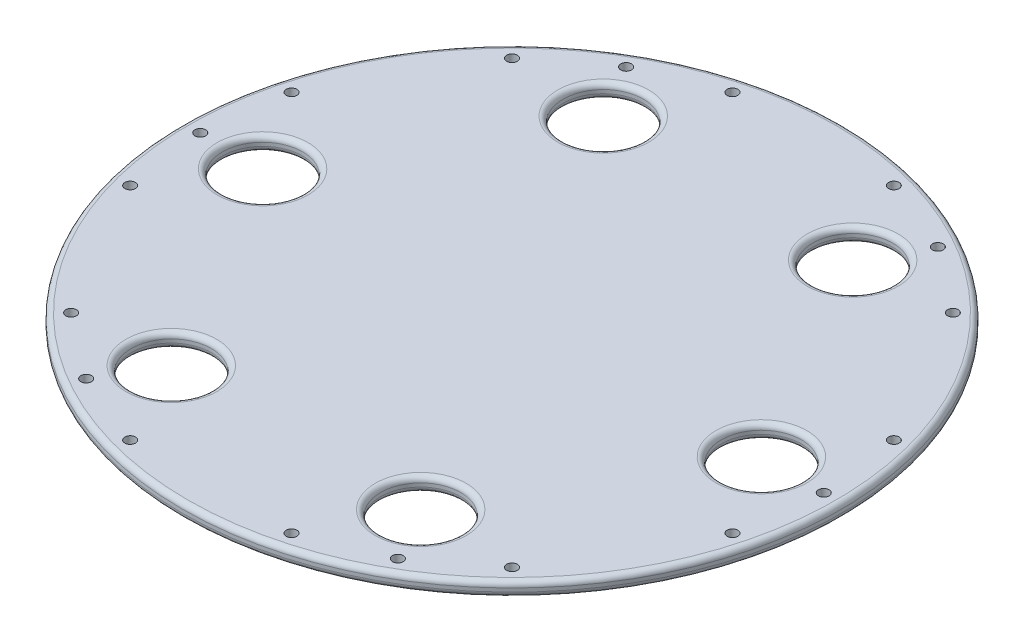
SolidWorks part; units mm, degrees
ref_plane "Front Plane" through (0, 0, 0) normal (0, 0, 1) x (1, 0, 0)
ref_plane "Top Plane" through (0, 0, 0) normal (0, 1, 0) x (1, 0, 0)
ref_plane "Right Plane" through (0, 0, 0) normal (1, 0, 0) x (0, 0, -1)
sketch "Sketch1" plane through (0, 0, 0) normal (0, 1, 0) x (1, 0, 0)
  circle A0 centre (0, 0) radius 92.5
  dimension "D1" = 185
extrude "Boss-Extrude1" add sketch "Sketch1" along normal blind 4
sketch "Sketch2" plane through (0, 4, 0) normal (0, 1, 0) x (1, 0, 0)
  line L0 (0, 0) -> (-51, 0)
  line L1 (0, 0) -> (-43.75, 75.7772)
  line L4 (0, 0) -> (-7, 0)
  line L5 (0, 0) -> (-35, 60.6218)
  circle A3 centre (-43.75, 75.7772) radius 1.5
  circle A4 centre (-22.6467, 84.5185) radius 1.5
  circle A5 centre (-61.8718, 61.8718) radius 1.5
  circle A6 centre (43.75, 75.7772) radius 1.5
  circle A7 centre (22.6467, 84.5185) radius 1.5
  circle A8 centre (61.8718, 61.8718) radius 1.5
  circle A9 centre (87.5, 0) radius 1.5
  circle A10 centre (84.5185, 22.6467) radius 1.5
  circle A11 centre (84.5185, -22.6467) radius 1.5
  circle A13 centre (-35, 60.6218) radius 11.25
  circle A23 centre (35, 60.6218) radius 11.25
  circle A24 centre (70, 0) radius 11.25
  circle A25 centre (43.75, -75.7772) radius 1.5
  circle A26 centre (61.8718, -61.8718) radius 1.5
  circle A27 centre (22.6467, -84.5185) radius 1.5
  circle A28 centre (-43.75, -75.7772) radius 1.5
  circle A29 centre (-22.6467, -84.5185) radius 1.5
  circle A30 centre (-61.8718, -61.8718) radius 1.5
  circle A31 centre (-87.5, 0) radius 1.5
  circle A32 centre (-84.5185, -22.6467) radius 1.5
  circle A33 centre (-84.5185, 22.6467) radius 1.5
  circle A34 centre (35, -60.6218) radius 11.25
  circle A35 centre (-35, -60.6218) radius 11.25
  circle A36 centre (-70, 0) radius 11.25
  point P10 (0, 0)
  point P15 (0, 0)
  point P18 (0, 0)
  point P32 (0, 0)
  point P33 (0, 0)
  point P41 (0, 0)
  point P46 (0, 0)
  point P49 (0, 0)
  point P55 (0, 0)
  dimension "D1" = 70
  dimension "D2" = 6
  dimension "D5" = 2
  dimension "D6" = 2
  dimension "D7" = 3
  dimension "D8" = 6
  dimension "D4" = 22.5
  dimension "D3" = 60
extrude "Cut-Extrude1" cut sketch "Sketch2" against normal through all
fillet "Fillet1" radius 1.5 14 edges at (0, 4, 92.5) (0, 0, 92.5) (35, 4, -49.3718) (35, 0, -49.3718) (-35, 4, -49.3718) (-35, 0, -49.3718) (70, 4, 11.25) (70, 0, 11.25) (35, 4, 71.8718) (35, 0, 71.8718) (-35, 4, 71.8718) (-35, 0, 71.8718) (-70, 4, 11.25) (-70, 0, 11.25)
